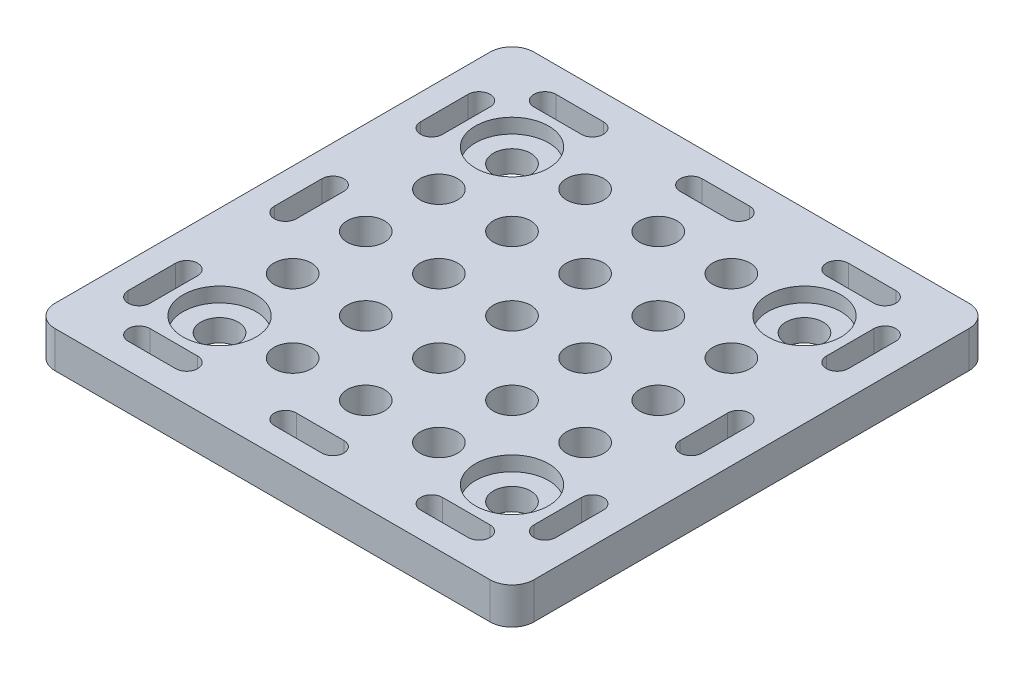
SolidWorks part; units mm, degrees
material "6061-T6 (SS)"
ref_plane "Front Plane" through (0, 0, 0) normal (0, 0, 1) x (1, 0, 0)
ref_plane "Top Plane" through (0, 0, 0) normal (0, 1, 0) x (1, 0, 0)
ref_plane "Right Plane" through (0, 0, 0) normal (1, 0, 0) x (0, 0, -1)
sketch "Sketch1" plane through (0, 0, 0) normal (0, 1, 0) x (1, 0, 0)
  line L0 (0, 0) -> (32.75, 0) construction
  line L1 (29.75, -32.75) -> (-29.75, -32.75)
  line L2 (32.75, -29.75) -> (32.75, 29.75)
  line L3 (29.75, 32.75) -> (-29.75, 32.75)
  line L4 (-32.75, -29.75) -> (-32.75, 29.75)
  line L5 (0, 32.75) -> (0, 0) construction
  line L6 (-27.75, 16.75) -> (-27.75, 23.25) construction
  line L7 (-29.25, 16.75) -> (-29.25, 23.25)
  line L8 (-26.25, 16.75) -> (-26.25, 23.25)
  line L9 (27.75, 16.75) -> (27.75, 23.25) construction
  line L10 (26.25, 16.75) -> (26.25, 23.25)
  line L11 (29.25, 16.75) -> (29.25, 23.25)
  line L12 (3.25, 27.75) -> (-3.25, 27.75) construction
  line L13 (3.25, 26.25) -> (-3.25, 26.25)
  line L14 (3.25, 29.25) -> (-3.25, 29.25)
  line L15 (-16.75, 27.75) -> (-23.25, 27.75) construction
  line L16 (-16.75, 26.25) -> (-23.25, 26.25)
  line L17 (-16.75, 29.25) -> (-23.25, 29.25)
  line L18 (16.75, 27.75) -> (23.25, 27.75) construction
  line L19 (16.75, 26.25) -> (23.25, 26.25)
  line L20 (16.75, 29.25) -> (23.25, 29.25)
  line L21 (27.75, -3.25) -> (27.75, 3.25) construction
  line L22 (26.25, -3.25) -> (26.25, 3.25)
  line L23 (29.25, -3.25) -> (29.25, 3.25)
  line L24 (-16.75, -27.75) -> (-23.25, -27.75) construction
  line L25 (-16.75, -26.25) -> (-23.25, -26.25)
  line L26 (-16.75, -29.25) -> (-23.25, -29.25)
  line L27 (3.25, -27.75) -> (-3.25, -27.75) construction
  line L28 (3.25, -26.25) -> (-3.25, -26.25)
  line L29 (3.25, -29.25) -> (-3.25, -29.25)
  line L30 (16.75, -27.75) -> (23.25, -27.75) construction
  line L31 (16.75, -26.25) -> (23.25, -26.25)
  line L32 (16.75, -29.25) -> (23.25, -29.25)
  line L33 (27.75, -23.25) -> (27.75, -16.75) construction
  line L34 (26.25, -23.25) -> (26.25, -16.75)
  line L35 (29.25, -23.25) -> (29.25, -16.75)
  line L36 (-27.75, -3.25) -> (-27.75, 3.25) construction
  line L37 (-29.25, -3.25) -> (-29.25, 3.25)
  line L38 (-26.25, -3.25) -> (-26.25, 3.25)
  line L39 (-27.75, -23.25) -> (-27.75, -16.75) construction
  line L40 (-29.25, -23.25) -> (-29.25, -16.75)
  line L41 (-26.25, -23.25) -> (-26.25, -16.75)
  arc A0 (-29.75, -32.75) -> (-32.75, -29.75) centre (-29.75, -29.75) cw
  arc A1 (29.75, -32.75) -> (32.75, -29.75) centre (29.75, -29.75) ccw
  arc A2 (32.75, 29.75) -> (29.75, 32.75) centre (29.75, 29.75) ccw
  arc A3 (-29.75, 32.75) -> (-32.75, 29.75) centre (-29.75, 29.75) ccw
  arc A4 (-29.25, 16.75) -> (-26.25, 16.75) centre (-27.75, 16.75) ccw
  arc A5 (-26.25, 23.25) -> (-29.25, 23.25) centre (-27.75, 23.25) ccw
  circle A6 centre (0, 0) radius 2.55
  arc A7 (26.25, 16.75) -> (29.25, 16.75) centre (27.75, 16.75) ccw
  circle A8 centre (10, -10) radius 2.55
  circle A9 centre (20, -10) radius 2.55
  arc A10 (29.25, 23.25) -> (26.25, 23.25) centre (27.75, 23.25) ccw
  circle A11 centre (10, -20) radius 2.55
  circle A12 centre (20, -20) radius 2.55
  arc A13 (26.25, -3.25) -> (29.25, -3.25) centre (27.75, -3.25) ccw
  arc A14 (29.25, 3.25) -> (26.25, 3.25) centre (27.75, 3.25) ccw
  arc A15 (26.25, -23.25) -> (29.25, -23.25) centre (27.75, -23.25) ccw
  arc A16 (29.25, -16.75) -> (26.25, -16.75) centre (27.75, -16.75) ccw
  arc A17 (-29.25, -3.25) -> (-26.25, -3.25) centre (-27.75, -3.25) ccw
  arc A18 (-26.25, 3.25) -> (-29.25, 3.25) centre (-27.75, 3.25) ccw
  circle A19 centre (-10, -10) radius 2.55
  circle A20 centre (-20, -10) radius 2.55
  arc A21 (-29.25, -23.25) -> (-26.25, -23.25) centre (-27.75, -23.25) ccw
  circle A22 centre (-10, -20) radius 2.55
  circle A23 centre (-20, -20) radius 2.55
  arc A24 (-26.25, -16.75) -> (-29.25, -16.75) centre (-27.75, -16.75) ccw
  circle A25 centre (0, -10) radius 2.55
  circle A26 centre (0, -20) radius 2.55
  circle A27 centre (10, 0) radius 2.55
  circle A28 centre (20, 0) radius 2.55
  circle A30 centre (10, 10) radius 2.55
  circle A31 centre (20, 10) radius 2.55
  circle A33 centre (10, 20) radius 2.55
  circle A34 centre (20, 20) radius 2.55
  circle A38 centre (-10, 0) radius 2.55
  circle A39 centre (-20, 0) radius 2.55
  circle A41 centre (-10, 10) radius 2.55
  circle A42 centre (-20, 10) radius 2.55
  circle A44 centre (-10, 20) radius 2.55
  circle A45 centre (-20, 20) radius 2.55
  circle A47 centre (0, 10) radius 2.55
  circle A48 centre (0, 20) radius 2.55
  arc A69 (3.25, 26.25) -> (3.25, 29.25) centre (3.25, 27.75) ccw
  arc A70 (-3.25, 29.25) -> (-3.25, 26.25) centre (-3.25, 27.75) ccw
  arc A71 (-16.75, 26.25) -> (-16.75, 29.25) centre (-16.75, 27.75) ccw
  arc A72 (-23.25, 29.25) -> (-23.25, 26.25) centre (-23.25, 27.75) ccw
  arc A73 (16.75, 26.25) -> (16.75, 29.25) centre (16.75, 27.75) cw
  arc A74 (23.25, 29.25) -> (23.25, 26.25) centre (23.25, 27.75) cw
  arc A77 (-16.75, -26.25) -> (-16.75, -29.25) centre (-16.75, -27.75) cw
  arc A78 (-23.25, -29.25) -> (-23.25, -26.25) centre (-23.25, -27.75) cw
  arc A79 (3.25, -26.25) -> (3.25, -29.25) centre (3.25, -27.75) cw
  arc A80 (-3.25, -29.25) -> (-3.25, -26.25) centre (-3.25, -27.75) cw
  arc A81 (16.75, -26.25) -> (16.75, -29.25) centre (16.75, -27.75) ccw
  arc A82 (23.25, -29.25) -> (23.25, -26.25) centre (23.25, -27.75) ccw
  circle A83 centre (0, -10) radius 2.55 [skipped]
  circle A84 centre (0, -20) radius 2.55 [skipped]
  circle A85 centre (10, 0) radius 2.55 [skipped]
  circle A86 centre (20, 0) radius 2.55 [skipped]
  circle A87 centre (30, 0) radius 2.55 [skipped]
  circle A88 centre (-10, 0) radius 2.55 [skipped]
  circle A89 centre (-20, 0) radius 2.55 [skipped]
  circle A90 centre (-30, 0) radius 2.55 [skipped]
  circle A91 centre (0, 10) radius 2.55 [skipped]
  circle A92 centre (0, 20) radius 2.55 [skipped]
  circle A93 centre (-30, -10) radius 2.55 [skipped]
  circle A94 centre (-30, -20) radius 2.55 [skipped]
  circle A95 centre (-30, 0) radius 2.55 [skipped]
  circle A96 centre (-30, 10) radius 2.55 [skipped]
  circle A97 centre (-30, 20) radius 2.55 [skipped]
  circle A98 centre (30, -10) radius 2.55 [skipped]
  circle A99 centre (30, -20) radius 2.55 [skipped]
  circle A100 centre (30, 0) radius 2.55 [skipped]
  circle A101 centre (30, 10) radius 2.55 [skipped]
  circle A102 centre (30, 20) radius 2.55 [skipped]
  point P0 (0, 0)
  point P3 (-27.75, 20)
  point P37 (27.75, 20)
  point P44 (27.75, 0)
  point P59 (27.75, -20)
  point P82 (-27.75, 0)
  point P97 (-27.75, -20)
  point P156 (0, 27.75)
  point P162 (-20, 27.75)
  point P170 (20, 27.75)
  point P184 (-20, -27.75)
  point P191 (0, -27.75)
  point P198 (20, -27.75)
  dimension "D2" = 3
  dimension "D3" = 5
  dimension "D5" = 3
  dimension "D7" = 3
  dimension "D10" = 4
  dimension "D14" = 6.5
  dimension "D4" = 3
  dimension "D6" = 4
  dimension "D8" = 3
  dimension "65.5" = 65.5
  dimension "D9" = 65.5
  dimension "D11" = 4
  dimension "D12" = 4
  dimension "D13" = 20
  dimension "D15" = 3
  dimension "D16" = 5
  dimension "D17" = 12.75
  dimension "D18" = 3
  dimension "D27" = 6.5
  dimension "D28" = 3
extrude "Boss-Extrude1" add sketch "Sketch1" along normal blind 5
sketch "草圖4" plane through (0, 5, 0) normal (0, 1, 0) x (1, 0, 0)
  circle A0 centre (-20, -20) radius 5
  circle A1 centre (20, -20) radius 5
  circle A2 centre (20, 20) radius 5
  circle A3 centre (-20, 20) radius 5
  dimension "D1" = 2
extrude "除料-伸長1" cut sketch "草圖4" against normal blind 2
